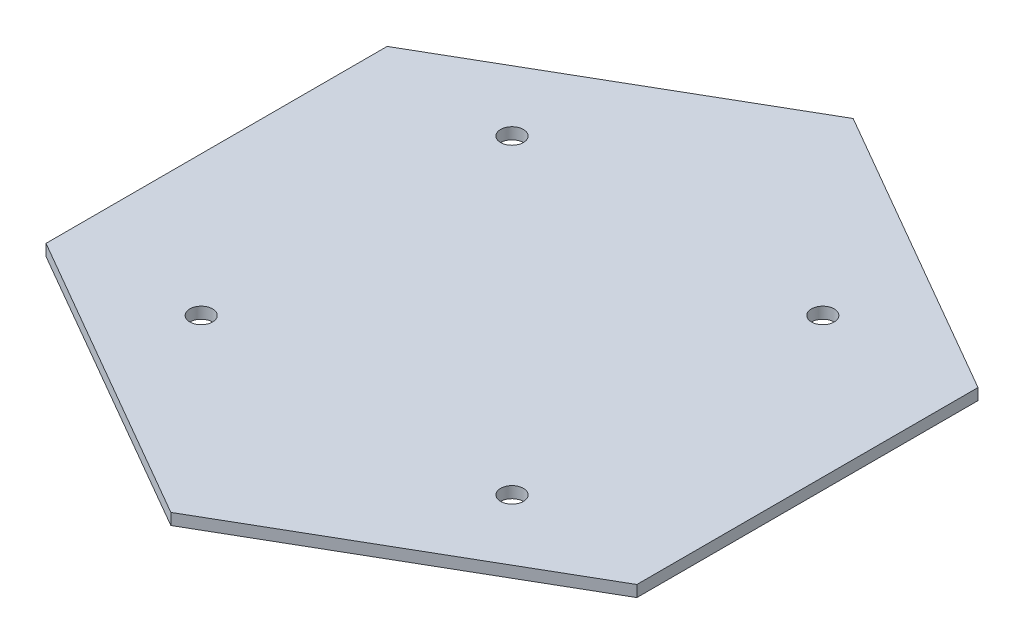
SolidWorks part; units mm, degrees
ref_plane "Front Plane" through (0, 0, 0) normal (0, 0, 1) x (1, 0, 0)
ref_plane "Top Plane" through (0, 0, 0) normal (0, 1, 0) x (1, 0, 0)
ref_plane "Right Plane" through (0, 0, 0) normal (1, 0, 0) x (0, 0, -1)
sketch "Sketch1" plane through (0, 0, 0) normal (0, 1, 0) x (1, 0, 0)
  line L1 (0, -45) -> (38.9711, -22.5)
  line L2 (38.9711, -22.5) -> (38.9711, 22.5)
  line L3 (38.9711, 22.5) -> (0, 45)
  line L4 (0, 45) -> (-38.9711, 22.5)
  line L5 (-38.9711, 22.5) -> (-38.9711, -22.5)
  line L6 (-38.9711, -22.5) -> (0, -45)
  circle A0 centre (0, 0) radius 38.9711 construction
extrude "Boss-Extrude1" add sketch "Sketch1" along normal blind 1.5
sketch "Sketch2" plane through (0, 1.5, 0) normal (0, 1, 0) x (1, 0, 0)
  circle A0 centre (20.5, 20.5) radius 1.5
  circle A1 centre (20.5, -20.5) radius 1.5
  circle A2 centre (-20.5, -20.5) radius 1.5
  circle A3 centre (-20.5, 20.5) radius 1.5
  point P14 (0, 0)
  point P15 (0, 0)
extrude "Cut-Extrude1" cut sketch "Sketch2" against normal blind 1.5
